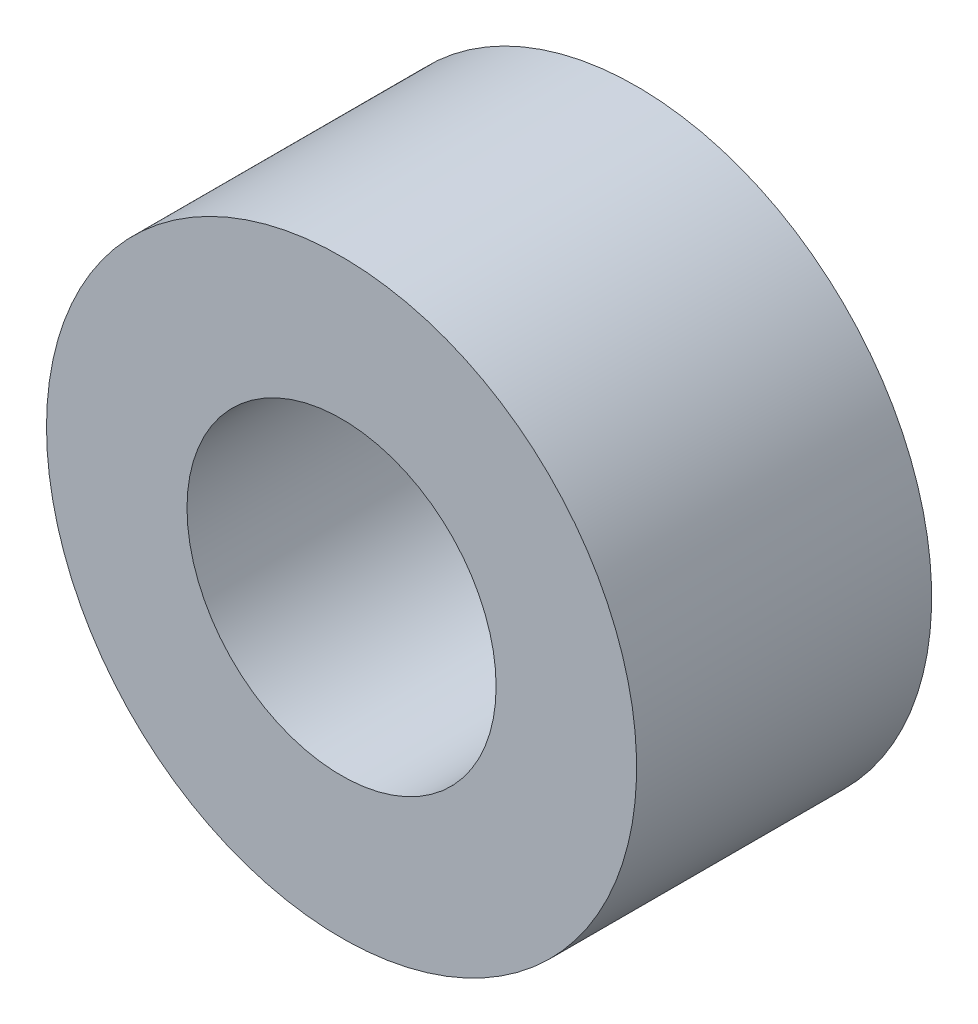
SolidWorks part; units mm, degrees
ref_plane "Plan de face" through (0, 0, 0) normal (0, 0, 1) x (1, 0, 0)
ref_plane "Plan de dessus" through (0, 0, 0) normal (0, 1, 0) x (1, 0, 0)
ref_plane "Plan de droite" through (0, 0, 0) normal (1, 0, 0) x (0, 0, -1)
sketch "Esquisse1" plane through (0, 0, 0) normal (0, 0, 1) x (1, 0, 0)
  circle A0 centre (0, 0) radius 5.5
  circle A1 centre (0, 0) radius 10.5
  dimension "D1" = 11
  dimension "D2" = 5
extrude "Boss.-Extru.1" add sketch "Esquisse1" along normal blind 10.5
